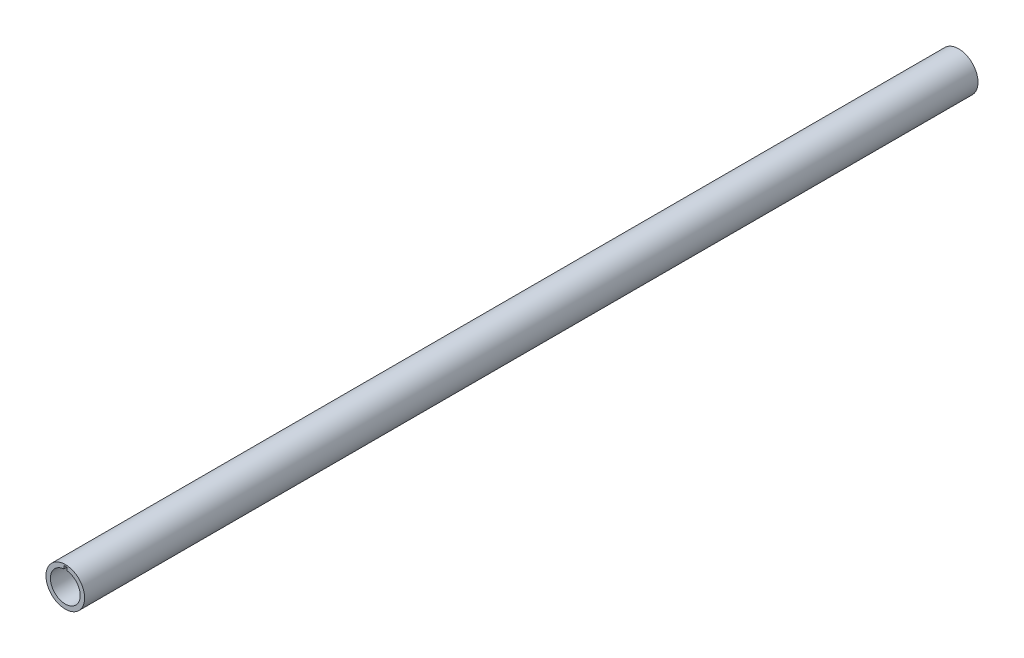
SolidWorks part; units mm, degrees
ref_plane "Front Plane" through (0, 0, 0) normal (0, 0, 1) x (1, 0, 0)
ref_plane "Top Plane" through (0, 0, 0) normal (0, 1, 0) x (1, 0, 0)
ref_plane "Right Plane" through (0, 0, 0) normal (1, 0, 0) x (0, 0, -1)
sketch "Sketch1" plane through (0, 0, 0) normal (0, 0, 1) x (1, 0, 0)
  circle A0 centre (0, 0) radius 10
  circle A1 centre (0, 0) radius 13
  dimension "D1" = 20
  dimension "D2" = 26
extrude "Boss-Extrude1" add sketch "Sketch1" along normal blind 600
sketch "Sketch2" plane through (0, 0, 600) normal (0, 0, 1) x (1, 0, 0)
  line L0 (0, 0) -> (0, 10) construction
  line L1 (0, 10) -> (-1, 10) construction
  line L4 (-1, 9.9499) -> (-1, 12)
  line L5 (-1, 12) -> (1, 12)
  line L6 (1, 9.9499) -> (1, 12)
  circle A0 centre (0, 0) radius 10 construction
  arc A1 (1, 9.9499) -> (-1, 9.9499) centre (0, 0) ccw
  dimension "D1" = 1
  dimension "D2" = 1
  dimension "D3" = 2
extrude "Cut-Extrude1" cut sketch "Sketch2" against normal blind 20
sketch "Sketch3" plane through (0, 0, 0) normal (0, 0, -1) x (-1, 0, 0)
  line L0 (0, 0) -> (0, 10) construction
  line L4 (-1, 9.9499) -> (-1, 11.9499)
  line L5 (-1, 11.9499) -> (1, 11.9499)
  line L6 (1, 9.9499) -> (1, 11.9499)
  circle A0 centre (0, 0) radius 10 construction
  arc A1 (1, 9.9499) -> (-1, 9.9499) centre (0, 0) ccw
  dimension "D1" = 2
  dimension "D2" = 2
  dimension "D3" = 1
extrude "Cut-Extrude2" cut sketch "Sketch3" against normal blind 20
